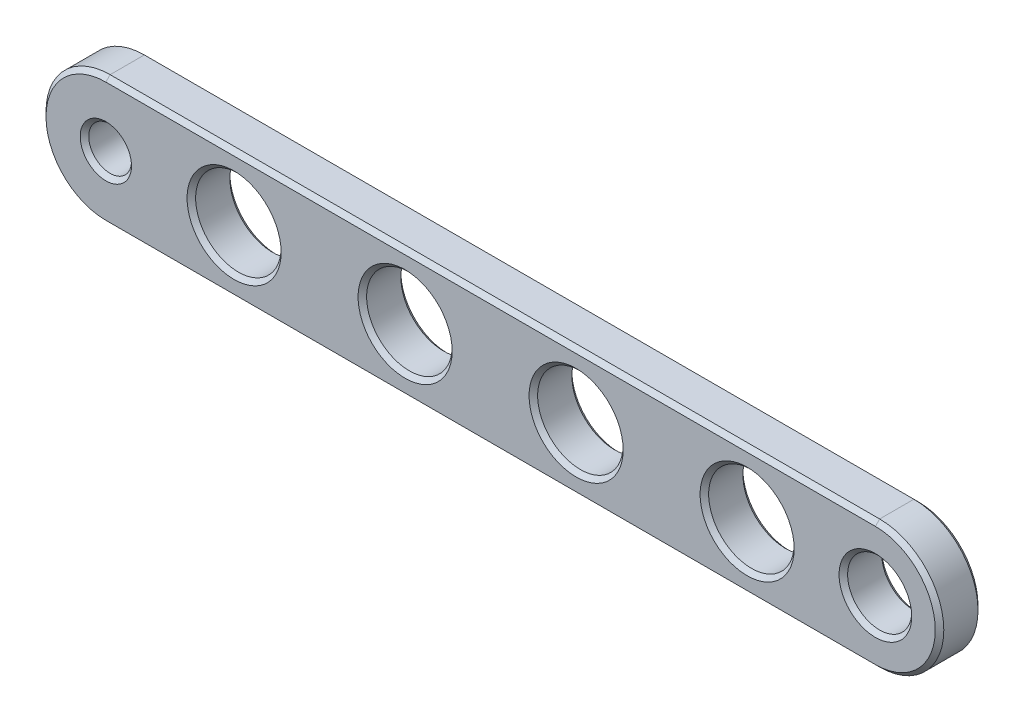
SolidWorks part; units mm, degrees
ref_plane "Front Plane" through (0, 0, 0) normal (0, 0, 1) x (1, 0, 0)
ref_plane "Top Plane" through (0, 0, 0) normal (0, 1, 0) x (1, 0, 0)
ref_plane "Right Plane" through (0, 0, 0) normal (1, 0, 0) x (0, 0, -1)
sketch "Sketch1" plane through (0, 0, 0) normal (0, 0, 1) x (1, 0, 0)
  line L0 (-18, 0) -> (18, 0) construction
  line L1 (-18, 3) -> (18, 3)
  line L2 (-18, -3) -> (18, -3)
  arc A0 (-18, 3) -> (-18, -3) centre (-18, 0) ccw
  arc A1 (18, -3) -> (18, 3) centre (18, 0) ccw
  circle A2 centre (-18, 0) radius 1
  circle A3 centre (18, 0) radius 1.5
  circle A4 centre (-12, 0) radius 2
  circle A5 centre (-4, 0) radius 2
  circle A6 centre (4, 0) radius 2
  circle A7 centre (12, 0) radius 2
  point P3 (0, 0)
  dimension "D2" = 2
  dimension "D3" = 3
  dimension "D4" = 3
  dimension "D5" = 4
  dimension "D1" = 36
  dimension "D6" = 6
  dimension "D7" = 2
  dimension "D8" = 2
  dimension "D9" = 2
extrude "Boss-Extrude1" add sketch "Sketch1" along normal blind 2
chamfer "Chamfer1" distance 0.2 angle 45 20 edges at (14, 0, 0) (6, 0, 0) (-2, 0, 0) (-10, 0, 0) (19.5, 0, 0) (-17, 0, 0) (0, -3, 0) (21, 0, 0) (0, 3, 0) (-21, 0, 0) (14, 0, 2) (-2, 0, 2) (19.5, 0, 2) (0, 3, 2) (21, 0, 2) (0, -3, 2) (-21, 0, 2) (-17, 0, 2) (-10, 0, 2) (6, 0, 2)
